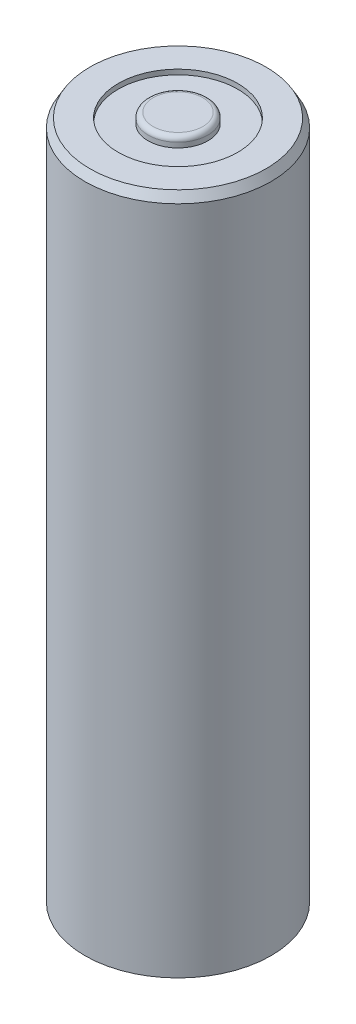
SolidWorks part; units mm, degrees
other "Kamera1"
ref_plane "Płaszczyzna przednia" through (0, 0, 0) normal (0, 0, 1) x (1, 0, 0)
ref_plane "Płaszczyzna górna" through (0, 0, 0) normal (0, 1, 0) x (1, 0, 0)
ref_plane "Płaszczyzna prawa" through (0, 0, 0) normal (1, 0, 0) x (0, 0, -1)
sketch "Szkic1" plane through (0, 0, 0) normal (0, 1, 0) x (1, 0, 0)
  circle A0 centre (0, 0) radius 9.35
  dimension "D1" = 18.7
extrude "Dodanie-wyciągnięcie1" add sketch "Szkic1" along normal blind 68.2
sketch "Szkic2" plane through (0, 0, 0) normal (0, -1, 0) x (1, 0, 0)
  circle A0 centre (0, 0) radius 7
  dimension "D1" = 14
extrude "Wytnij-wyciągnięcie1" cut sketch "Szkic2" against normal blind 0.5
sketch "Szkic3" plane through (0, 68.2, 0) normal (0, 1, 0) x (1, 0, 0)
  circle A0 centre (0, 0) radius 6
  dimension "D1" = 12
extrude "Wytnij-wyciągnięcie2" cut sketch "Szkic3" against normal blind 0.5
sketch "Szkic4" plane through (0, 67.7, 0) normal (0, 1, 0) x (1, 0, 0)
  circle A0 centre (0, 0) radius 3
  dimension "D1" = 6
extrude "Dodanie-wyciągnięcie2" add sketch "Szkic4" along normal blind 1
fillet "Zaokrąglenie1" radius 0.5 1 edges at (0, 68.7, 3)
chamfer "Sfazowanie1" distance 0.5 angle 60 1 edges at (0, 68.2, 9.35)
